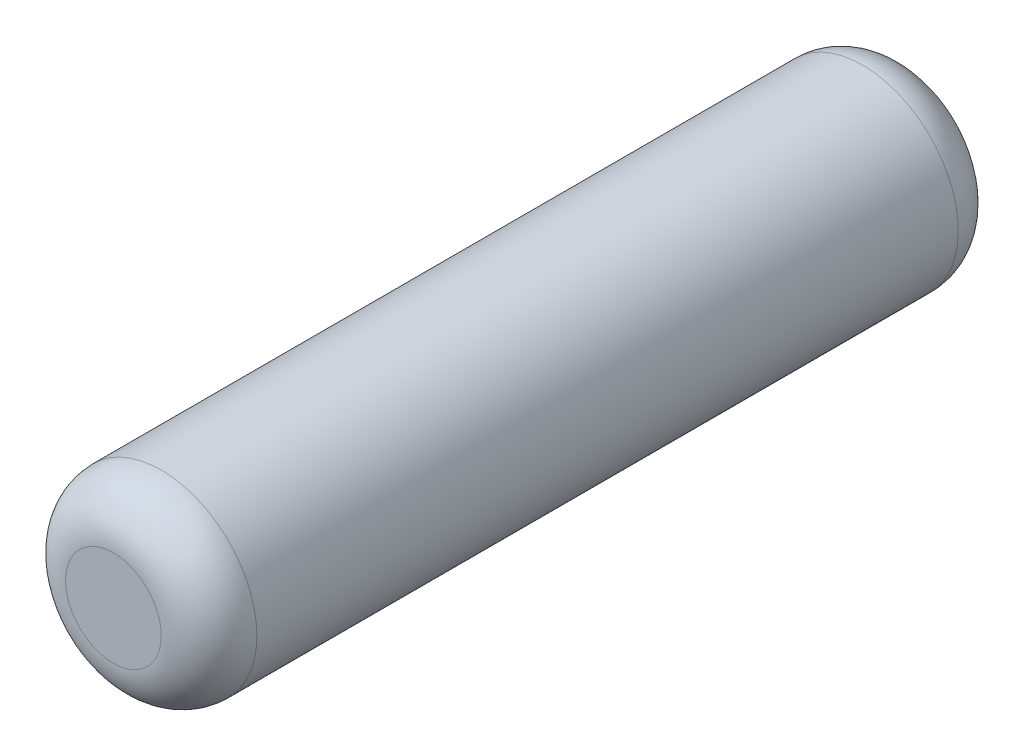
SolidWorks part; units mm, degrees
ref_plane "Front Plane" through (0, 0, 0) normal (0, 0, 1) x (1, 0, 0)
ref_plane "Top Plane" through (0, 0, 0) normal (0, 1, 0) x (1, 0, 0)
ref_plane "Right Plane" through (0, 0, 0) normal (1, 0, 0) x (0, 0, -1)
sketch "Sketch1" plane through (0, 0, 0) normal (0, 0, 1) x (1, 0, 0)
  circle A0 centre (0, 0) radius 3
  dimension "D1" = 6
extrude "Boss-Extrude1" add sketch "Sketch1" along normal blind 25
fillet "Fillet1" radius 1.5 2 edges at (3, 0, 0) (3, 0, 25)
